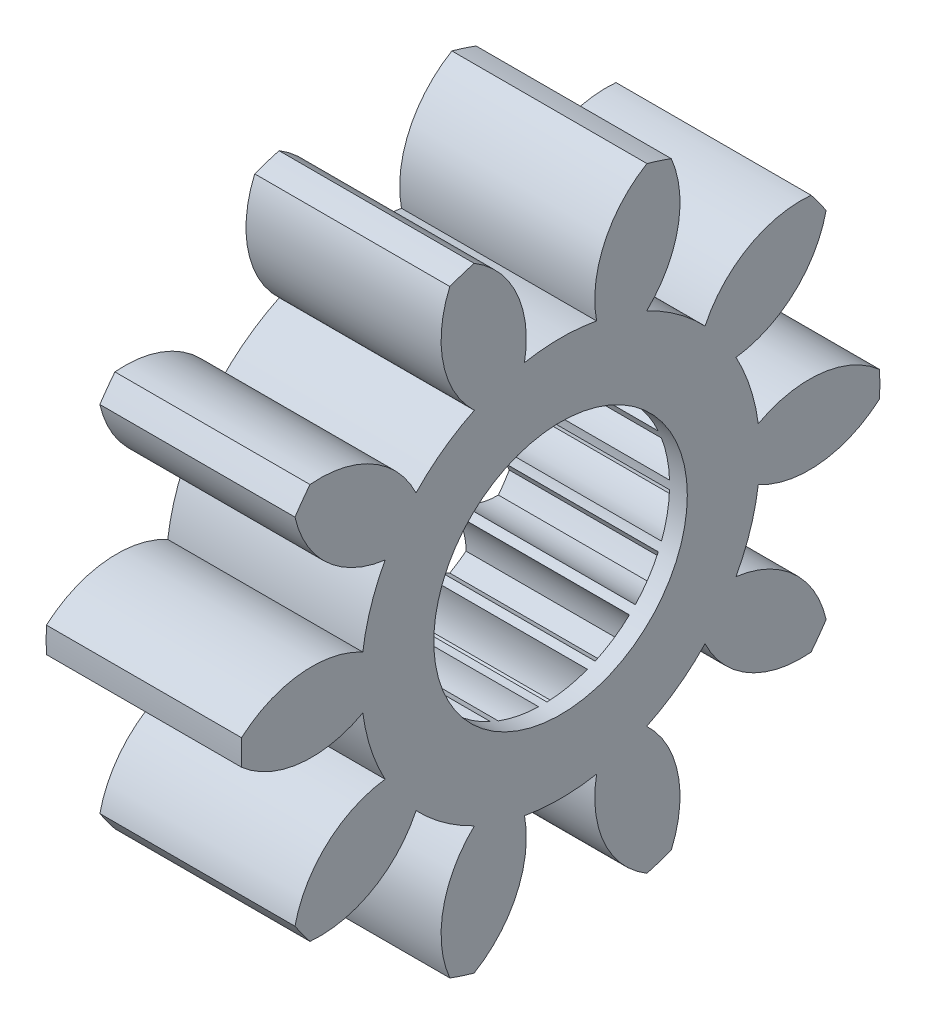
SolidWorks part; units mm, degrees
material "PET"
ref_plane "Plane1" through (0, 0, 0) normal (0, 0, 1) x (1, 0, 0)
ref_plane "Plane2" through (0, 0, 0) normal (0, 1, 0) x (1, 0, 0)
ref_plane "Plane3" through (0, 0, 0) normal (1, 0, 0) x (0, 0, -1)
sketch "HoldingSke" plane through (0, 0, 0) normal (0, 1, 0) x (1, 0, 0)
  line L0 (0, 0) -> (0.6565, -0.1158)
  line L1 (-15, 0) -> (100, 0) construction
  line L2 (0, 0) -> (-2.1039, 2.3779)
  line L3 (0, 0) -> (-11.863, 4.5341)
  line L4 (0, 0) -> (8.5048, 1.4996)
  line L5 (0, 0) -> (-46.8476, -17.4728)
  line L6 (0, 0) -> (-4.1448, -2.7965)
  line L7 (-2.1039, 2.3779) -> (8.6586, 51.2059)
  line L8 (-76.2, 54.61) -> (-75.9, 54.61)
  line L9 (-67.7845, 28.3722) -> (-49.3413, 33.142)
  line L10 (-76.2, 71.12) -> (104.1128, 71.12)
  line L11 (0, 0) -> (-5, 0)
  line L12 (-76.2, 101.6) -> (-76.147, 101.6)
  line L13 (24.9733, 27.94) -> (52.9518, 28.4284)
  line L14 (24.9733, 27.94) -> (24.9743, 27.94)
  line L15 (24.9733, 27.94) -> (100.4006, 29.5858)
  line L16 (-63.627, -1.5) -> (-12.827, -1.5)
  circle A0 centre (0, 0) radius 1
  circle A1 centre (0, 0) radius 5.624
  circle A2 centre (0, 0) radius 37.5
  circle A3 centre (0, 0) radius 1
  dimension "MHD" = 11.248
  dimension "Hub_dia" = 75
  dimension "Bore" = 2
  dimension "MBD" = 2
  dimension "Num_teeth" = 10
  dimension "Pitch" = 0.6667
  dimension "Overall_len" = 50
  dimension "Show_teeth" = 10
  dimension "Thickness" = 5
  dimension "OAL" = 50.0001
  dimension "T_dim" = 0.3
  dimension "Ap" = 14.5
  dimension "H" = 19.05
  dimension "Pitch_radius" = 180.3128
  dimension "Width" = 5
  dimension "Backlash" = 0.053
  dimension "Addendum_fac" = 1
  dimension "Dedendum_fac" = 1.25
  dimension "Clearance_fac" = 0.25
  dimension "Dedendum_add" = 0.001
  dimension "Module" = 1.5
sketch "BasProSke" plane through (0, 0, 0) normal (0, 1, 0) x (1, 0, 0)
  line L0 (-10, 0) -> (60, 0) construction
  line L1 (0, 0) -> (0, 9)
  line L2 (0, 0) -> (5, 0)
  line L3 (5, 0) -> (5, 9)
  line L4 (5, 9) -> (0, 9)
  dimension "Thickness" = 5
  dimension "Diameter" = 18
revolve "Base-Revolve" add sketch "BasProSke" angle 360 about L0
sketch "TooCutSke" plane through (0, 0, 0) normal (1, 0, 0) x (0, 0, -1)
  line L1 (0, 0) -> (0, 107) construction
  line L2 (0, 0) -> (-1.2658, 7.3924) construction
  line L3 (0, 0) -> (-4.5869, 14.117) construction
  line L4 (-1.2658, 7.3924) -> (-2.2934, 7.0585) construction
  arc A0 (1.0161, 5.5314) -> (-1.0161, 5.5314) centre (0, 0) ccw
  arc A1 (2.4664, 8.6819) -> (-2.4664, 8.6819) centre (0, 0) ccw
  circle A2 centre (0, 0) radius 7.5 construction
  circle A3 centre (0, 0) radius 7.2611 construction
  arc A4 (-1.0161, 5.5314) -> (-2.4664, 8.6819) centre (-3.965, 6.083) ccw
  arc A5 (2.4664, 8.6819) -> (1.0161, 5.5314) centre (3.965, 6.083) ccw
  dimension "Root_dia" = 11.248
  dimension "Overcut_dia" = 18.0508
  dimension "Pitch_dia" = 15
  dimension "Base_dia" = 14.5222
  dimension "Flank_rad" = 3
  dimension "Half_ang" = 18
  dimension "Half_CT" = 1.0805
extrude "ToothCut" cut sketch "TooCutSke" along normal through all
fillet "Breaks" [suppressed] radius 0.03
fillet "RootFillets" [suppressed] radius 0.376
pattern_circular "TeethCuts" count 10 every 36 about axis through (-10, 0, 0) along (1, 0, 0) of "ToothCut", "RootFillets", "Breaks"
sketch "HubNeaOneSke" plane through (0, 0, 0) normal (-1, 0, 0) x (0, 0, 1)
  circle A0 centre (0, 0) radius 5.624
  dimension "Diameter" = 11.248
extrude "HubNearOne" [suppressed] add sketch "HubNeaOneSke" along normal blind 45.0001
sketch "HubNeaBotSke" plane through (0, 0, 0) normal (-1, 0, 0) x (0, 0, 1)
  circle A0 centre (0, 0) radius 5.624
  dimension "Diameter" = 11.248
extrude "HubNearBoth" [suppressed] add sketch "HubNeaBotSke" along normal blind 22.5
ref_plane "FarPln" through (5, 0, 0) normal (1, 0, 0) x (0, 0, -1)
sketch "HubFarSke" plane through (5, 0, 0) normal (1, 0, 0) x (0, 0, -1)
  circle A0 centre (0, 0) radius 5.624
  dimension "Diameter" = 11.248
extrude "HubFar" [suppressed] add sketch "HubFarSke" along normal blind 22.5
sketch "BorSke" plane through (0, 0, 0) normal (1, 0, 0) x (0, 0, -1)
  circle A0 centre (0, 0) radius 1
  dimension "Diameter" = 2
extrude "Bore" cut sketch "BorSke" along normal mid plane 100.0001
sketch "KeySke" plane through (0, 0, 0) normal (1, 0, 0) x (0, 0, -1)
  line L0 (-0.4, 0) -> (-0.4, 1.3)
  line L1 (-0.4, 1.3) -> (0.4, 1.3)
  line L2 (0.4, 1.3) -> (0.4, 0)
  line L3 (0, 0) -> (0, 34) construction
  line L4 (-0.4, 0) -> (0.4, 0)
  dimension "Offset" = 1.3
  dimension "Width" = 0.8
extrude "Keyway" [suppressed] cut sketch "KeySke" along normal mid plane 100.0001
pattern_circular "Keyway2" [suppressed] count 2 every 90 about axis through (-10, 0, 0) along (1, 0, 0)
sketch "Schizzo1" plane through (5, 0, 0) normal (1, 0, 0) x (0, 0, -1)
  arc A0 (-0.1172, 3.5721) -> (-0.645, 4.6555) centre (-1.906, 3.3711) ccw
  arc A1 (0.1172, 3.5721) -> (-0.1172, 3.5721) centre (0, 0) ccw
  arc A2 (0.645, 4.6555) -> (0.1172, 3.5721) centre (1.906, 3.3711) ccw
  arc A3 (1.1857, 4.548) -> (0.645, 4.6555) centre (0, 0) ccw
  arc A4 (1.2587, 3.345) -> (1.1857, 4.548) centre (-0.4708, 3.8439) ccw
  arc A5 (1.4753, 3.2553) -> (1.2587, 3.345) centre (0, 0) ccw
  arc A6 (2.3775, 4.0543) -> (1.4753, 3.2553) centre (3.051, 2.3851) ccw
  arc A7 (2.8359, 3.748) -> (2.3775, 4.0543) centre (0, 0) ccw
  arc A8 (2.4429, 2.6087) -> (2.8359, 3.748) centre (1.036, 3.7314) ccw
  arc A9 (2.6087, 2.4429) -> (2.4429, 2.6087) centre (0, 0) ccw
  arc A10 (3.748, 2.8359) -> (2.6087, 2.4429) centre (3.7314, 1.036) ccw
  arc A11 (4.0543, 2.3775) -> (3.748, 2.8359) centre (0, 0) ccw
  arc A12 (3.2553, 1.4753) -> (4.0543, 2.3775) centre (2.3851, 3.051) ccw
  arc A13 (3.345, 1.2587) -> (3.2553, 1.4753) centre (0, 0) ccw
  arc A14 (4.548, 1.1857) -> (3.345, 1.2587) centre (3.8439, -0.4708) ccw
  arc A15 (4.6555, 0.645) -> (4.548, 1.1857) centre (0, 0) ccw
  arc A16 (3.5721, 0.1172) -> (4.6555, 0.645) centre (3.3711, 1.906) ccw
  arc A17 (3.5721, -0.1172) -> (3.5721, 0.1172) centre (0, 0) ccw
  arc A18 (4.6555, -0.645) -> (3.5721, -0.1172) centre (3.3711, -1.906) ccw
  arc A19 (4.548, -1.1857) -> (4.6555, -0.645) centre (0, 0) ccw
  arc A20 (3.345, -1.2587) -> (4.548, -1.1857) centre (3.8439, 0.4708) ccw
  arc A21 (3.2553, -1.4753) -> (3.345, -1.2587) centre (0, 0) ccw
  arc A22 (4.0543, -2.3775) -> (3.2553, -1.4753) centre (2.3851, -3.051) ccw
  arc A23 (3.748, -2.8359) -> (4.0543, -2.3775) centre (0, 0) ccw
  arc A24 (2.6087, -2.4429) -> (3.748, -2.8359) centre (3.7314, -1.036) ccw
  arc A25 (2.4429, -2.6087) -> (2.6087, -2.4429) centre (0, 0) ccw
  arc A26 (2.8359, -3.748) -> (2.4429, -2.6087) centre (1.036, -3.7314) ccw
  arc A27 (2.3775, -4.0543) -> (2.8359, -3.748) centre (0, 0) ccw
  arc A28 (1.4753, -3.2553) -> (2.3775, -4.0543) centre (3.051, -2.3851) ccw
  arc A29 (1.2587, -3.345) -> (1.4753, -3.2553) centre (0, 0) ccw
  arc A30 (1.1857, -4.548) -> (1.2587, -3.345) centre (-0.4708, -3.8439) ccw
  arc A31 (0.645, -4.6555) -> (1.1857, -4.548) centre (0, 0) ccw
  arc A32 (0.1172, -3.5721) -> (0.645, -4.6555) centre (1.906, -3.3711) ccw
  arc A33 (-0.1172, -3.5721) -> (0.1172, -3.5721) centre (0, 0) ccw
  arc A34 (-0.645, -4.6555) -> (-0.1172, -3.5721) centre (-1.906, -3.3711) ccw
  arc A35 (-1.1857, -4.548) -> (-0.645, -4.6555) centre (0, 0) ccw
  arc A36 (-1.2587, -3.345) -> (-1.1857, -4.548) centre (0.4708, -3.8439) ccw
  arc A37 (-1.4753, -3.2553) -> (-1.2587, -3.345) centre (0, 0) ccw
  arc A38 (-2.3775, -4.0543) -> (-1.4753, -3.2553) centre (-3.051, -2.3851) ccw
  arc A39 (-2.8359, -3.748) -> (-2.3775, -4.0543) centre (0, 0) ccw
  arc A40 (-2.4429, -2.6087) -> (-2.8359, -3.748) centre (-1.036, -3.7314) ccw
  arc A41 (-2.6087, -2.4429) -> (-2.4429, -2.6087) centre (0, 0) ccw
  arc A42 (-3.748, -2.8359) -> (-2.6087, -2.4429) centre (-3.7314, -1.036) ccw
  arc A43 (-4.0543, -2.3775) -> (-3.748, -2.8359) centre (0, 0) ccw
  arc A44 (-3.2553, -1.4753) -> (-4.0543, -2.3775) centre (-2.3851, -3.051) ccw
  arc A45 (-3.345, -1.2587) -> (-3.2553, -1.4753) centre (0, 0) ccw
  arc A46 (-4.548, -1.1857) -> (-3.345, -1.2587) centre (-3.8439, 0.4708) ccw
  arc A47 (-4.6555, -0.645) -> (-4.548, -1.1857) centre (0, 0) ccw
  arc A48 (-3.5721, -0.1172) -> (-4.6555, -0.645) centre (-3.3711, -1.906) ccw
  arc A49 (-3.5721, 0.1172) -> (-3.5721, -0.1172) centre (0, 0) ccw
  arc A50 (-4.6555, 0.645) -> (-3.5721, 0.1172) centre (-3.3711, 1.906) ccw
  arc A51 (-4.548, 1.1857) -> (-4.6555, 0.645) centre (0, 0) ccw
  arc A52 (-3.345, 1.2587) -> (-4.548, 1.1857) centre (-3.8439, -0.4708) ccw
  arc A53 (-3.2553, 1.4753) -> (-3.345, 1.2587) centre (0, 0) ccw
  arc A54 (-4.0543, 2.3775) -> (-3.2553, 1.4753) centre (-2.3851, 3.051) ccw
  arc A55 (-3.748, 2.8359) -> (-4.0543, 2.3775) centre (0, 0) ccw
  arc A56 (-2.6087, 2.4429) -> (-3.748, 2.8359) centre (-3.7314, 1.036) ccw
  arc A57 (-2.4429, 2.6087) -> (-2.6087, 2.4429) centre (0, 0) ccw
  arc A58 (-2.8359, 3.748) -> (-2.4429, 2.6087) centre (-1.036, 3.7314) ccw
  arc A59 (-2.3775, 4.0543) -> (-2.8359, 3.748) centre (0, 0) ccw
  arc A60 (-1.4753, 3.2553) -> (-2.3775, 4.0543) centre (-3.051, 2.3851) ccw
  arc A61 (-1.2587, 3.345) -> (-1.4753, 3.2553) centre (0, 0) ccw
  arc A62 (-1.1857, 4.548) -> (-1.2587, 3.345) centre (0.4708, 3.8439) ccw
  arc A63 (-0.645, 4.6555) -> (-1.1857, 4.548) centre (0, 0) ccw
  circle A64 centre (0, 0) radius 1 construction
  point P128 (0, 0)
extrude "Taglio-Estrusione1" cut sketch "Schizzo1" against normal through all
sketch "Schizzo2" plane through (5, 0, 0) normal (1, 0, 0) x (0, 0, -1)
  circle A0 centre (0, 0) radius 3.574
  circle A1 centre (0, 0) radius 5.624
extrude "Estrusione-Estrusione1" add sketch "Schizzo2" along normal blind 0.5
sketch "Schizzo3" plane through (5, 0, 0) normal (1, 0, 0) x (0, 0, -1)
  arc A0 (-1.0161, 5.5314) -> (-2.4293, 5.0723) centre (0, 0) ccw construction
  arc A1 (-1.0161, 5.5314) -> (-2.4359, 8.6641) centre (-3.965, 6.083) ccw construction
  arc A2 (-2.4359, 8.6641) -> (-3.1219, 8.4412) centre (0, 0) ccw construction
  arc A3 (-3.1219, 8.4412) -> (-2.4293, 5.0723) centre (-0.3678, 7.2518) ccw construction
  arc A4 (2.4293, 5.0723) -> (1.0161, 5.5314) centre (0, 0) ccw
  arc A5 (2.4293, 5.0723) -> (3.1219, 8.4412) centre (0.3678, 7.2518) ccw
  arc A6 (3.1219, 8.4412) -> (2.4359, 8.6641) centre (0, 0) ccw
  arc A7 (2.4359, 8.6641) -> (1.0161, 5.5314) centre (3.965, 6.083) ccw
  arc A8 (2.4293, 5.0723) -> (1.0161, 5.5314) centre (0, 0) ccw
  arc A9 (2.4293, 5.0723) -> (3.1219, 8.4412) centre (0.3678, 7.2518) ccw
  arc A10 (3.1219, 8.4412) -> (2.4359, 8.6641) centre (0, 0) ccw
  arc A11 (2.4359, 8.6641) -> (1.0161, 5.5314) centre (3.965, 6.083) ccw
  arc A12 (-4.0734, 3.8778) -> (-4.9467, 2.6757) centre (0, 0) ccw construction
  arc A13 (-4.0734, 3.8778) -> (-7.0633, 5.5776) centre (-6.7832, 2.5907) ccw construction
  arc A14 (-7.0633, 5.5776) -> (-7.4873, 4.9941) centre (0, 0) ccw construction
  arc A15 (-7.4873, 4.9941) -> (-4.9467, 2.6757) centre (-4.56, 5.6507) ccw construction
  arc A16 (-5.5747, 0.7429) -> (-5.5747, -0.7429) centre (0, 0) ccw construction
  arc A17 (-5.5747, 0.7429) -> (-8.9928, 0.3606) centre (-7.0105, -1.8912) ccw construction
  arc A18 (-8.9928, 0.3606) -> (-8.9928, -0.3606) centre (0, 0) ccw construction
  arc A19 (-8.9928, -0.3606) -> (-5.5747, -0.7429) centre (-7.0105, 1.8912) ccw construction
  arc A20 (-4.9467, -2.6757) -> (-4.0734, -3.8778) centre (0, 0) ccw construction
  arc A21 (-4.9467, -2.6757) -> (-7.4873, -4.9941) centre (-4.56, -5.6507) ccw construction
  arc A22 (-7.4873, -4.9941) -> (-7.0633, -5.5776) centre (0, 0) ccw construction
  arc A23 (-7.0633, -5.5776) -> (-4.0734, -3.8778) centre (-6.7832, -2.5907) ccw construction
  arc A24 (-2.4293, -5.0723) -> (-1.0161, -5.5314) centre (0, 0) ccw construction
  arc A25 (-2.4293, -5.0723) -> (-3.1219, -8.4412) centre (-0.3678, -7.2518) ccw construction
  arc A26 (-3.1219, -8.4412) -> (-2.4359, -8.6641) centre (0, 0) ccw construction
  arc A27 (-2.4359, -8.6641) -> (-1.0161, -5.5314) centre (-3.965, -6.083) ccw construction
  arc A28 (1.0161, -5.5314) -> (2.4293, -5.0723) centre (0, 0) ccw construction
  arc A29 (1.0161, -5.5314) -> (2.4359, -8.6641) centre (3.965, -6.083) ccw construction
  arc A30 (2.4359, -8.6641) -> (3.1219, -8.4412) centre (0, 0) ccw construction
  arc A31 (3.1219, -8.4412) -> (2.4293, -5.0723) centre (0.3678, -7.2518) ccw construction
  arc A32 (4.0734, -3.8778) -> (4.9467, -2.6757) centre (0, 0) ccw construction
  arc A33 (4.0734, -3.8778) -> (7.0633, -5.5776) centre (6.7832, -2.5907) ccw construction
  arc A34 (7.0633, -5.5776) -> (7.4873, -4.9941) centre (0, 0) ccw construction
  arc A35 (7.4873, -4.9941) -> (4.9467, -2.6757) centre (4.56, -5.6507) ccw construction
  arc A36 (5.5747, -0.7429) -> (5.5747, 0.7429) centre (0, 0) ccw construction
  arc A37 (5.5747, -0.7429) -> (8.9928, -0.3606) centre (7.0105, 1.8912) ccw construction
  arc A38 (8.9928, -0.3606) -> (8.9928, 0.3606) centre (0, 0) ccw construction
  arc A39 (8.9928, 0.3606) -> (5.5747, 0.7429) centre (7.0105, -1.8912) ccw construction
  arc A40 (4.9467, 2.6757) -> (4.0734, 3.8778) centre (0, 0) ccw construction
  arc A41 (4.9467, 2.6757) -> (7.4873, 4.9941) centre (4.56, 5.6507) ccw construction
  arc A42 (7.4873, 4.9941) -> (7.0633, 5.5776) centre (0, 0) ccw construction
  arc A43 (7.0633, 5.5776) -> (4.0734, 3.8778) centre (6.7832, 2.5907) ccw construction
  arc A44 (-1.0161, 5.5314) -> (-2.4293, 5.0723) centre (0, 0) ccw
  arc A45 (-1.0161, 5.5314) -> (-2.4359, 8.6641) centre (-3.965, 6.083) ccw
  arc A46 (-2.4359, 8.6641) -> (-3.1219, 8.4412) centre (0, 0) ccw
  arc A47 (-3.1219, 8.4412) -> (-2.4293, 5.0723) centre (-0.3678, 7.2518) ccw
  arc A48 (-4.0734, 3.8778) -> (-4.9467, 2.6757) centre (0, 0) ccw
  arc A49 (-4.0734, 3.8778) -> (-7.0633, 5.5776) centre (-6.7832, 2.5907) ccw
  arc A50 (-7.0633, 5.5776) -> (-7.4873, 4.9941) centre (0, 0) ccw
  arc A51 (-7.4873, 4.9941) -> (-4.9467, 2.6757) centre (-4.56, 5.6507) ccw
  arc A52 (-5.5747, 0.7429) -> (-5.5747, -0.7429) centre (0, 0) ccw
  arc A53 (-5.5747, 0.7429) -> (-8.9928, 0.3606) centre (-7.0105, -1.8912) ccw
  arc A54 (-8.9928, 0.3606) -> (-8.9928, -0.3606) centre (0, 0) ccw
  arc A55 (-8.9928, -0.3606) -> (-5.5747, -0.7429) centre (-7.0105, 1.8912) ccw
  arc A56 (-4.9467, -2.6757) -> (-4.0734, -3.8778) centre (0, 0) ccw
  arc A57 (-4.9467, -2.6757) -> (-7.4873, -4.9941) centre (-4.56, -5.6507) ccw
  arc A58 (-7.4873, -4.9941) -> (-7.0633, -5.5776) centre (0, 0) ccw
  arc A59 (-7.0633, -5.5776) -> (-4.0734, -3.8778) centre (-6.7832, -2.5907) ccw
  arc A60 (-2.4293, -5.0723) -> (-1.0161, -5.5314) centre (0, 0) ccw
  arc A61 (-2.4293, -5.0723) -> (-3.1219, -8.4412) centre (-0.3678, -7.2518) ccw
  arc A62 (-3.1219, -8.4412) -> (-2.4359, -8.6641) centre (0, 0) ccw
  arc A63 (-2.4359, -8.6641) -> (-1.0161, -5.5314) centre (-3.965, -6.083) ccw
  arc A64 (1.0161, -5.5314) -> (2.4293, -5.0723) centre (0, 0) ccw
  arc A65 (1.0161, -5.5314) -> (2.4359, -8.6641) centre (3.965, -6.083) ccw
  arc A66 (2.4359, -8.6641) -> (3.1219, -8.4412) centre (0, 0) ccw
  arc A67 (3.1219, -8.4412) -> (2.4293, -5.0723) centre (0.3678, -7.2518) ccw
  arc A68 (4.0734, -3.8778) -> (4.9467, -2.6757) centre (0, 0) ccw
  arc A69 (4.0734, -3.8778) -> (7.0633, -5.5776) centre (6.7832, -2.5907) ccw
  arc A70 (7.0633, -5.5776) -> (7.4873, -4.9941) centre (0, 0) ccw
  arc A71 (7.4873, -4.9941) -> (4.9467, -2.6757) centre (4.56, -5.6507) ccw
  arc A72 (5.5747, -0.7429) -> (5.5747, 0.7429) centre (0, 0) ccw
  arc A73 (5.5747, -0.7429) -> (8.9928, -0.3606) centre (7.0105, 1.8912) ccw
  arc A74 (8.9928, -0.3606) -> (8.9928, 0.3606) centre (0, 0) ccw
  arc A75 (8.9928, 0.3606) -> (5.5747, 0.7429) centre (7.0105, -1.8912) ccw
  arc A76 (4.9467, 2.6757) -> (4.0734, 3.8778) centre (0, 0) ccw
  arc A77 (4.9467, 2.6757) -> (7.4873, 4.9941) centre (4.56, 5.6507) ccw
  arc A78 (7.4873, 4.9941) -> (7.0633, 5.5776) centre (0, 0) ccw
  arc A79 (7.0633, 5.5776) -> (4.0734, 3.8778) centre (6.7832, 2.5907) ccw
  dimension "D1" = 0
extrude "Estrusione-Estrusione2" add sketch "Schizzo3" along normal up to surface (0.5 mm away) up to face at (5.5, 0, -5.624)
sketch "Schizzo5" plane through (5.5, 0, 0) normal (1, 0, 0) x (0, 0, -1)
  circle A0 centre (0, 0) radius 7.5
  dimension "D1" = 15
equation "' \"Module@HoldingSke\" = 6.35"
equation "' \"Num_teeth@HoldingSke\" = 12"
equation "' \"Ap@HoldingSke\" =  20"
equation "' \"Ap@HoldingSke\" = 20"
equation "' \"Width@HoldingSke\" = 0.5 * 25.4"
equation "' \"Hub_dia@HoldingSke\"= 1 * 25.4"
equation "' \"Hub_dia@HoldingSke\" = 1 * 25.4"
equation "' \"Overall_len@HoldingSke\" = 1.0 * 25.4"
equation "' \"Bore@HoldingSke\" = 0.75 * 25.4"
equation "' \"T_dim@HoldingSke\" = 0.1 * 25.4"
equation "' \"Width@KeySke\" = 0.25 * 25.4"
equation "' \"Show_teeth@HoldingSke\" = 13"
equation "' \"Backlash@HoldingSke\" = 0.009 * 25.4"
equation "' \"Addendum_fac@HoldingSke\" = 1.0"
equation "' \"Dedendum_fac@HoldingSke\" = 1.25"
equation "' \"Dedendum_add@HoldingSke\" = 0.00005 * 25.4"
equation "' \"Clearance_fac@HoldingSke\" = 0.25"
equation "\"Pitch@HoldingSke\" = 1 / \"Module@HoldingSke\""
equation "\"Overcut_dia@TooCutSke\" = (\"Num_teeth@HoldingSke\" + 2 * \"Addendum_fac@HoldingSke\") / \"Pitch@HoldingSke\" + 0.002 * 25.4"
equation "\"Pitch_dia@TooCutSke\" = \"Num_teeth@HoldingSke\" / \"Pitch@HoldingSke\""
equation "\"Base_dia@TooCutSke\" = \"Num_teeth@HoldingSke\" / \"Pitch@HoldingSke\" * cos((\"Ap@HoldingSke\"  * 3.14159265 / 180))"
equation "\"Root_dia@TooCutSke\" = (\"Num_teeth@HoldingSke\" + 2) / \"Pitch@HoldingSke\" - 2 * (\"Addendum_fac@HoldingSke\" + \"Dedendum_fac@HoldingSke\") / \"Pitch@HoldingSke\" - \"Dedendum_add@HoldingSke\" * 2"
equation "\"Half_ang@TooCutSke\" = 180 / \"Num_teeth@HoldingSke\""
equation "\"Half_CT@TooCutSke\" = \"Num_teeth@HoldingSke\" / \"Pitch@HoldingSke\" * sin((3.14159265 / 2 / \"Num_teeth@HoldingSke\")) / 2 - 7 * \"Backlash@HoldingSke\" / 4"
equation "\"Flank_rad@TooCutSke\" = \"Num_teeth@HoldingSke\" / \"Pitch@HoldingSke\" / 5"
equation "\"Radius@RootFillets\" = \"Clearance_fac@HoldingSke\" / \"Pitch@HoldingSke\" + \"Dedendum_add@HoldingSke\""
equation "\"Break_rad@Breaks\" = 0.02 / \"Pitch@HoldingSke\""
equation "\"Thickness@HoldingSke\" = \"Width@HoldingSke\""
equation "\"OAL@HoldingSke\" = \"Thickness@HoldingSke\""
equation "\"MHD@HoldingSke\" = (\"Num_teeth@HoldingSke\" + 2) / \"Pitch@HoldingSke\" - 2 * (\"Addendum_fac@HoldingSke\" + \"Dedendum_fac@HoldingSke\")  / \"Pitch@HoldingSke\" - \"Dedendum_add@HoldingSke\" * 2"
equation "\"MBD@HoldingSke\" = (\"Num_teeth@HoldingSke\" + 2) / \"Pitch@HoldingSke\" - 2 * (\"Addendum_fac@HoldingSke\" + \"Dedendum_fac@HoldingSke\")  / \"Pitch@HoldingSke\" - \"Dedendum_add@HoldingSke\" * 2 - 0.002 * 25.4"
equation "\"MHD@HoldingSke\" = ((sgn( \"MHD@HoldingSke\" - \"Hub_dia@HoldingSke\" )-1)*( \"MHD@HoldingSke\" - \"Hub_dia@HoldingSke\" ))/-2+ \"Hub_dia@HoldingSke\""
equation "\"MBD@HoldingSke\" = ((sgn( \"MBD@HoldingSke\" - \"Bore@HoldingSke\" )-1)*( \"MBD@HoldingSke\" - \"Bore@HoldingSke\" ))/-2+ \"Bore@HoldingSke\""
equation "\"OAL@HoldingSke\" = ((sgn( \"OAL@HoldingSke\" - \"Overall_len@HoldingSke\" )+1)*( \"OAL@HoldingSke\" - \"Overall_len@HoldingSke\" ))/2 + \"Overall_len@HoldingSke\" + 0.000002 * 25.4"
equation "\"Num_teeth@TeethCuts\" = int( \"Show_teeth@HoldingSke\" ) + 1"
equation "\"Num_teeth@TeethCuts\" = ((sgn( \"Num_teeth@TeethCuts\" - \"Num_teeth@HoldingSke\" )-1)*( \"Num_teeth@TeethCuts\" - \"Num_teeth@HoldingSke\" ))/-2+ \"Num_teeth@HoldingSke\""
equation "\"Num_teeth@TeethCuts\" = ((sgn( \"Num_teeth@TeethCuts\" - 2.0)+1)*( \"Num_teeth@TeethCuts\" - 2.0))/2 +2.0"
equation "\"Angle@TeethCuts\" = 360.0 / \"Num_teeth@HoldingSke\""
equation "\"Diameter@BasProSke\" = (\"Num_teeth@HoldingSke\" + 2 * \"Addendum_fac@HoldingSke\") / \"Pitch@HoldingSke\""
equation "\"Thickness@BasProSke\"  = \"Thickness@HoldingSke\""
equation "' \"Fillet_rad@BasProSke\" =  \"Thickness@HoldingSke\" * 0.05"
equation "' \"Fillet_rad@BasProSke\" = \"Thickness@HoldingSke\" * 0.05"
equation "\"MHD@HoldingSke\" = ((sgn( \"MHD@HoldingSke\" - \"Root_dia@TooCutSke\" )-1)*( \"MHD@HoldingSke\" - \"Root_dia@TooCutSke\" ))/-2+ \"Root_dia@TooCutSke\""
equation "\"Diameter@HubNeaOneSke\" = \"MHD@HoldingSke\""
equation "\"Length@HubNearOne\" = \"OAL@HoldingSke\" - \"Thickness@BasProSke\""
equation "\"Diameter@HubNeaBotSke\" = \"MHD@HoldingSke\""
equation "\"Length@HubNearBoth\" = ( \"OAL@HoldingSke\" - \"Thickness@BasProSke\" ) / 2.0"
equation "\"Thickness@FarPln\" = \"Thickness@BasProSke\""
equation "\"Diameter@HubFarSke\" = \"MHD@HoldingSke\""
equation "\"Length@HubFar\" = ( \"OAL@HoldingSke\" - \"Thickness@BasProSke\" ) / 2.0"
equation "\"Diameter@BorSke\" = \"MBD@HoldingSke\""
equation "\"D1@Bore\" = \"OAL@HoldingSke\" * 2.0"
equation "\"D1@Keyway\" = \"OAL@HoldingSke\" * 2.0"
equation "\"Offset@KeySke\" = \"T_dim@HoldingSke\" + \"MBD@HoldingSke\" / 2.0"
